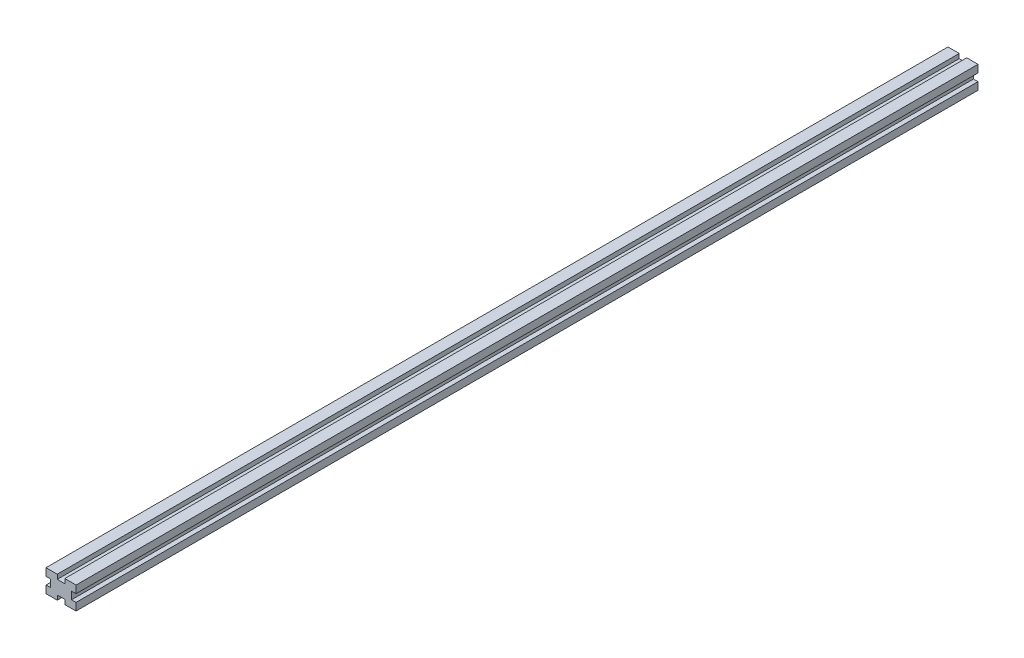
SolidWorks part; units mm, degrees
ref_plane "Front Plane" through (0, 0, 0) normal (0, 0, 1) x (1, 0, 0)
ref_plane "Top Plane" through (0, 0, 0) normal (0, 1, 0) x (1, 0, 0)
ref_plane "Right Plane" through (0, 0, 0) normal (1, 0, 0) x (0, 0, -1)
sketch "Sketch1" plane through (0, 0, 0) normal (0, 0, 1) x (1, 0, 0)
  line L1 (0, 0) -> (20, 0)
  line L2 (0, 0) -> (0, 15)
  line L3 (0, 15) -> (20, 15)
  line L4 (20, 0) -> (20, 15)
  dimension "D1" = 20
  dimension "D2" = 15
extrude "Boss-Extrude1" add sketch "Sketch1" along normal blind 600
sketch "Sketch2" plane through (0, 0, 600) normal (0, 0, 1) x (1, 0, 0)
  line L0 (20, 15) -> (0, 15) construction
  line L1 (7.5, 15) -> (12.5, 15)
  line L2 (7.5, 15) -> (7.5, 12)
  line L3 (7.5, 12) -> (12.5, 12)
  line L4 (12.5, 15) -> (12.5, 12)
  line L5 (20, 0) -> (20, 15) construction
  line L6 (20, 10) -> (17, 10)
  line L7 (20, 10) -> (20, 5)
  line L8 (20, 5) -> (17, 5)
  line L9 (17, 10) -> (17, 5)
  line L10 (0, 0) -> (20, 0) construction
  line L11 (12.5, 0) -> (7.5, 0)
  line L12 (12.5, 0) -> (12.5, 3)
  line L13 (12.5, 3) -> (7.5, 3)
  line L14 (7.5, 0) -> (7.5, 3)
  line L15 (0, 15) -> (0, 0) construction
  line L16 (0, 5) -> (3, 5)
  line L17 (0, 5) -> (0, 10)
  line L18 (0, 10) -> (3, 10)
  line L19 (3, 5) -> (3, 10)
  point P24 (10, 15)
  point P25 (10, 15)
  point P26 (10, 0)
  point P27 (20, 7.5)
  point P28 (20, 7.5)
  point P29 (0, 7.5)
  dimension "D1" = 5
  dimension "D2" = 3
  dimension "D3" = 5
  dimension "D4" = 5
  dimension "D5" = 3
  dimension "D6" = 3
extrude "Cut-Extrude1" cut sketch "Sketch2" against normal blind 700
